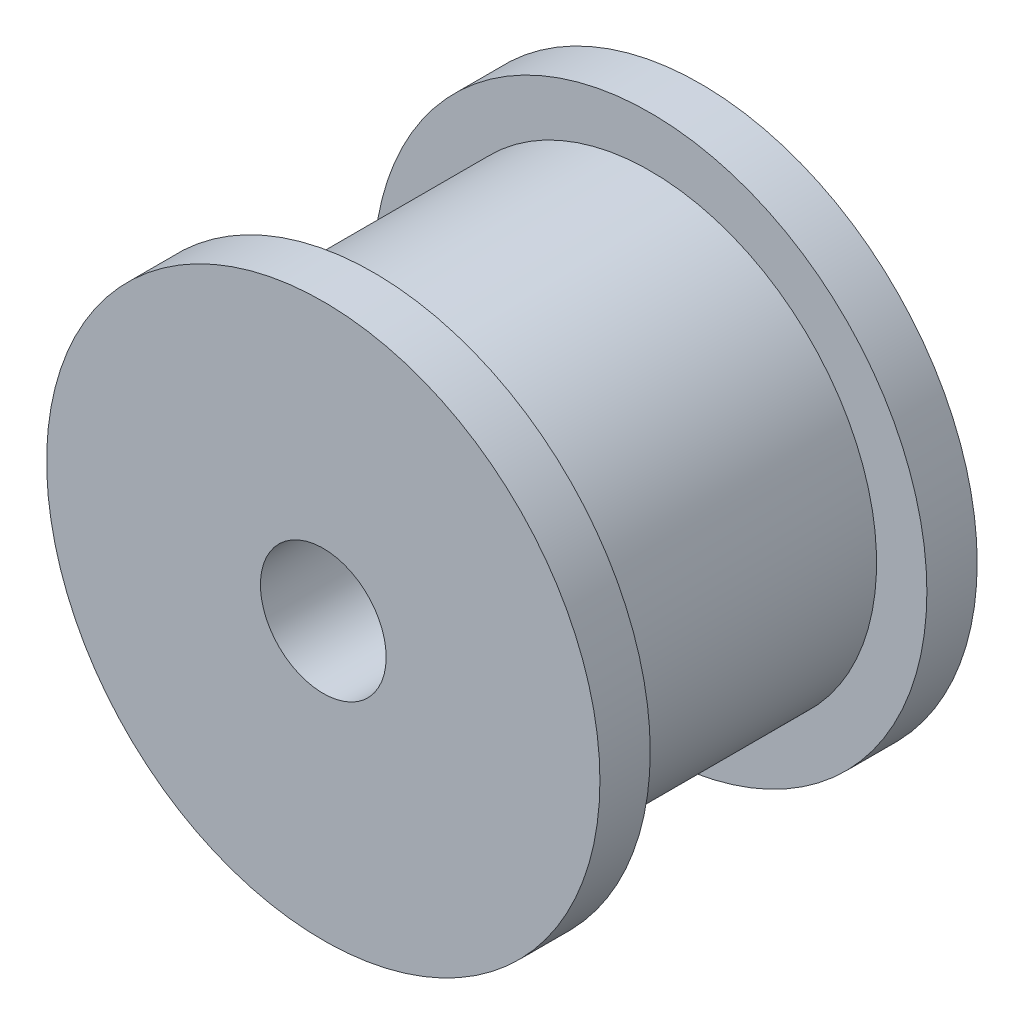
SolidWorks part; units mm, degrees
ref_plane "前视基准面" through (0, 0, 0) normal (0, 0, 1) x (1, 0, 0)
ref_plane "上视基准面" through (0, 0, 0) normal (0, 1, 0) x (1, 0, 0)
ref_plane "右视基准面" through (0, 0, 0) normal (1, 0, 0) x (0, 0, -1)
other "Configuration Table"
sketch "草图1" plane through (0, 0, 0) normal (0, 0, 1) x (1, 0, 0)
  circle A0 centre (0, 0) radius 9
  dimension "D1" = 18
extrude "凸台-拉伸1" add sketch "草图1" along normal blind 15
sketch "草图2" plane through (0, 0, 15) normal (0, 0, 1) x (1, 0, 0)
  circle A0 centre (0, 0) radius 11
  dimension "D1" = 22
extrude "凸台-拉伸2" add sketch "草图2" against normal blind 2
ref_plane "基准面1" through (0, 0, 7.5) normal (0, 0, -1) x (-1, 0, 0)
mirror "镜向1" about plane through (0, 0, 7.5) normal (0, 0, -1) of "凸台-拉伸2"
sketch "草图3" plane through (0, 0, 15) normal (0, 0, 1) x (1, 0, 0)
  circle A0 centre (0, 0) radius 2.5
  dimension "D1" = 5
extrude "切除-拉伸1" cut sketch "草图3" against normal through all
